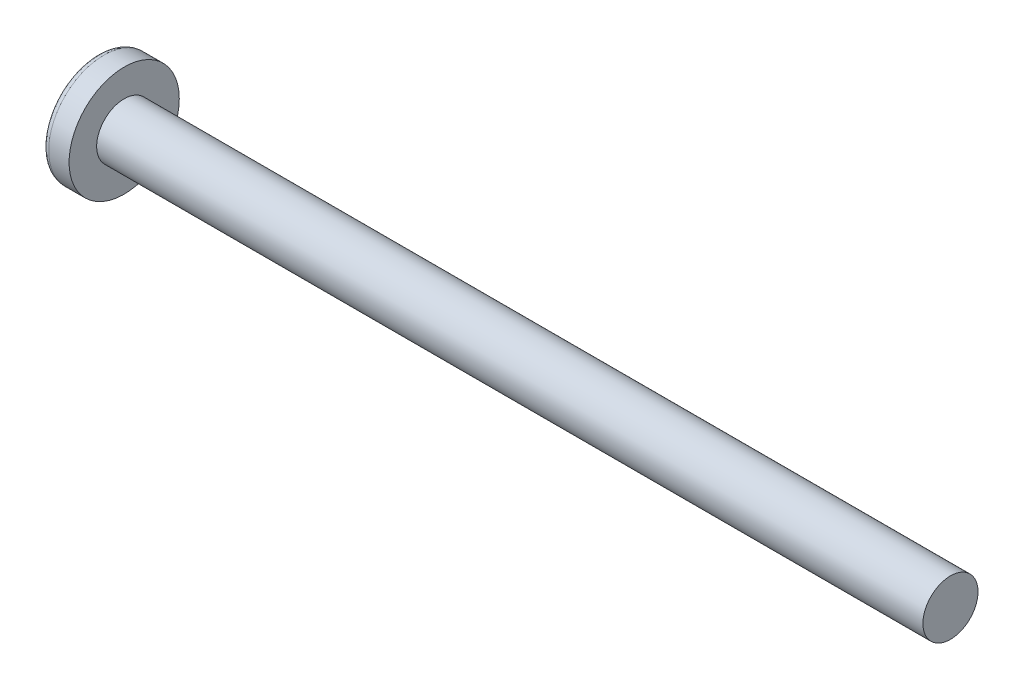
SolidWorks part; units mm, degrees
ref_plane "Front Plane" through (0, 0, 0) normal (0, 0, 1) x (1, 0, 0)
ref_plane "Top Plane" through (0, 0, 0) normal (0, 1, 0) x (1, 0, 0)
ref_plane "Right Plane" through (0, 0, 0) normal (1, 0, 0) x (0, 0, -1)
sketch "Sketch1" plane through (0, 0, 0) normal (0, 0, 1) x (1, 0, 0)
  line L0 (3.1, 2) -> (3.1, 4)
  line L1 (3.8, 6.35) -> (3.8, -3.175) construction
  line L2 (63.1, 0) -> (0, 0)
  line L3 (3.1, 2) -> (63.1, 2)
  line L4 (63.1, 2) -> (63.1, 0)
  line L5 (1.6164, 4) -> (3.1, 4)
  line L6 (3.1, -2) -> (63.1, -2) construction
  line L7 (3.1, 6.35) -> (3.1, -3.175) construction
  arc A0 (1.227, 3.8007) -> (0, 0) centre (6.5, 0) ccw
  arc A1 (1.227, 3.8007) -> (1.6164, 4) centre (1.6164, 3.52) cw
  dimension "D4" = 6.5
  dimension "D5" = 0.48
  dimension "D1" = 4
  dimension "D2" = 60
  dimension "D3" = 3.1
  dimension "D6" = 0.7
  dimension "D7" = 60
revolve "Revolve1" add sketch "Sketch1" angle 360 about L2
sketch "Sketch2" plane through (0, 0, 0) normal (1, 0, 0) x (0, 0, -1)
  line L0 (-0.5, -0.5) -> (-0.5, -1.9365)
  line L1 (-1.9365, 0.5) -> (-0.5, 0.5)
  line L2 (-1.9365, 0.5) -> (-1.9365, -0.5)
  line L3 (-1.9365, -0.5) -> (-0.5, -0.5)
  line L4 (1.9365, 0.5) -> (1.9365, -0.5)
  line L7 (-0.5, 1.9365) -> (0.5, 1.9365)
  line L8 (-0.5, 1.9365) -> (-0.5, 0.5)
  line L9 (-0.5, -1.9365) -> (0.5, -1.9365)
  line L10 (0.5, 1.9365) -> (0.5, 0.5)
  line L13 (0.5, -0.5) -> (0.5, -1.9365)
  line L14 (0.5, 0.5) -> (1.9365, 0.5)
  line L15 (0.5, -0.5) -> (1.9365, -0.5)
  circle A0 centre (0, 0) radius 2 construction
  circle A1 centre (0, 0) radius 2 construction
  dimension "D1" = 1
  dimension "D2" = 1
extrude "Cut-Extrude4" cut sketch "Sketch2" along normal blind 2.5
